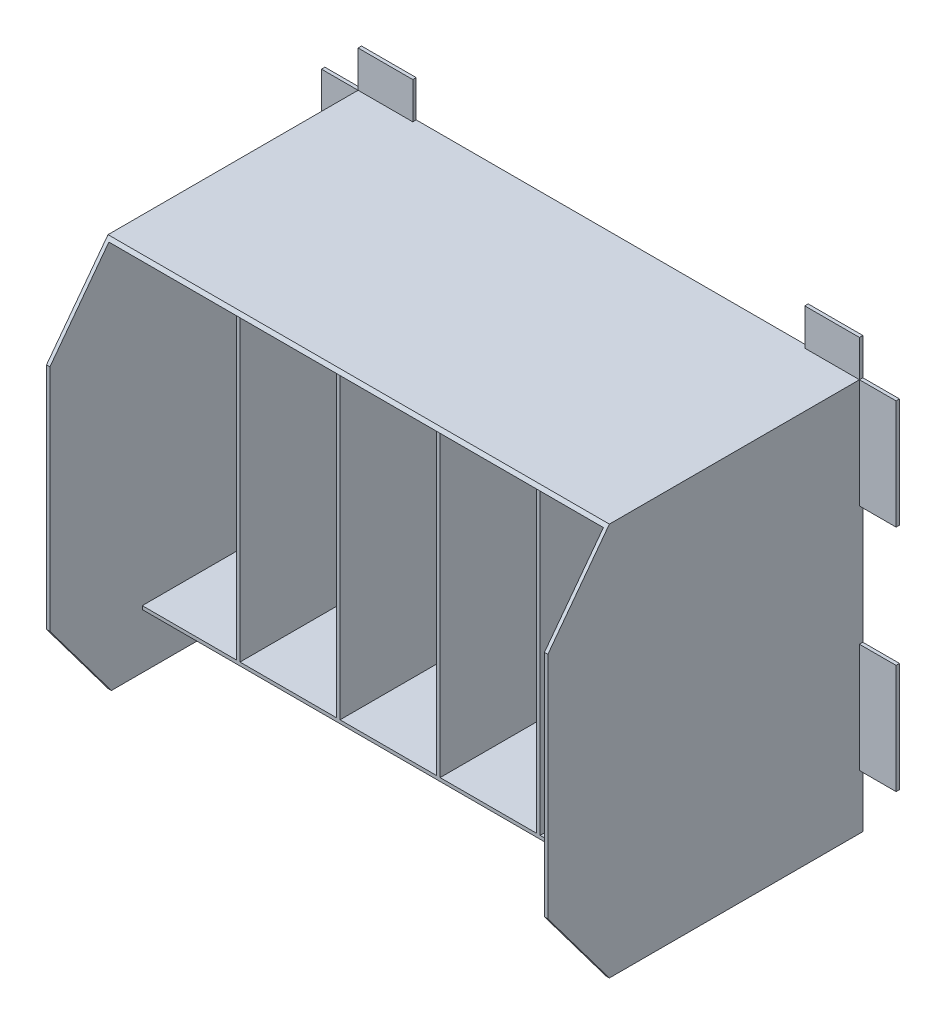
SolidWorks part; units mm, degrees
material "6061-T6 (SS)"
ref_plane "X-Y Datum" through (0, 0, 0) normal (0, 0, 1) x (1, 0, 0)
ref_plane "X-Z Datum" through (0, 0, 0) normal (0, 1, 0) x (1, 0, 0)
ref_plane "Y-Z Datum" through (0, 0, 0) normal (1, 0, 0) x (0, 0, -1)
sketch "Sketch1" plane through (0, 0, 0) normal (0, 0, 1) x (1, 0, 0)
  line L0 (-276.2265, 0) -> (276.2265, 0) construction
  line L1 (-276.2265, 154.041) -> (276.2265, 154.041)
  line L2 (-276.2265, 154.041) -> (-276.2265, -154.041)
  line L3 (-276.2265, -154.041) -> (276.2265, -154.041)
  line L4 (276.2265, 154.041) -> (276.2265, -154.041)
  line L5 (-276.2265, 154.041) -> (276.2265, -154.041) construction
  line L6 (-276.2265, -154.041) -> (276.2265, 154.041) construction
  line L7 (-275.2105, 153.025) -> (-189.6105, 153.025) construction
  line L8 (-275.2105, 153.025) -> (-275.2105, -153.025) construction
  line L9 (-275.2105, -153.025) -> (-189.6105, -153.025) construction
  line L10 (-189.6105, 153.025) -> (-189.6105, -153.025) construction
  line L11 (-275.2105, 153.025) -> (-189.6105, -153.025) construction
  line L12 (-275.2105, -153.025) -> (-189.6105, 153.025) construction
  line L13 (-188.5945, -154.041) -> (-188.5945, 154.041)
  line L14 (-279.4015, 157.216) -> (279.4015, 157.216)
  line L15 (279.4015, 157.216) -> (279.4015, -157.216)
  line L16 (-279.4015, -157.216) -> (279.4015, -157.216)
  line L17 (-279.4015, 157.216) -> (-279.4015, -157.216)
  line L18 (-185.4195, -154.041) -> (-185.4195, 154.041)
  line L19 (-188.5945, 0) -> (-185.4195, 0) construction
  line L20 (-182.2465, 153.025) -> (-182.2465, -153.025) construction
  line L21 (-182.2465, 153.025) -> (-96.6465, 153.025) construction
  line L22 (-96.6465, 153.025) -> (-96.6465, -153.025) construction
  line L23 (-182.2465, -153.025) -> (-96.6465, -153.025) construction
  line L24 (-95.6305, -154.041) -> (-95.6305, 154.041)
  line L25 (-92.4555, -154.041) -> (-92.4555, 154.041)
  line L26 (-89.2825, 153.025) -> (-89.2825, -153.025) construction
  line L27 (-89.2825, 153.025) -> (-3.6825, 153.025) construction
  line L28 (-3.6825, 153.025) -> (-3.6825, -153.025) construction
  line L29 (-89.2825, -153.025) -> (-3.6825, -153.025) construction
  line L30 (-2.6665, -154.041) -> (-2.6665, 154.041)
  line L31 (0.5085, -154.041) -> (0.5085, 154.041)
  line L32 (3.6815, 153.025) -> (3.6815, -153.025) construction
  line L33 (3.6815, 153.025) -> (89.2815, 153.025) construction
  line L34 (89.2815, 153.025) -> (89.2815, -153.025) construction
  line L35 (3.6815, -153.025) -> (89.2815, -153.025) construction
  line L36 (90.2975, -154.041) -> (90.2975, 154.041)
  line L37 (93.4725, -154.041) -> (93.4725, 154.041)
  line L38 (96.6455, 153.025) -> (96.6455, -153.025) construction
  line L39 (96.6455, 153.025) -> (182.2455, 153.025) construction
  line L40 (182.2455, 153.025) -> (182.2455, -153.025) construction
  line L41 (96.6455, -153.025) -> (182.2455, -153.025) construction
  line L42 (183.2615, -154.041) -> (183.2615, 154.041)
  line L43 (186.4365, -154.041) -> (186.4365, 154.041)
  line L44 (-182.2465, -153.025) -> (-96.6465, 153.025) construction
  line L45 (-182.2465, 153.025) -> (-96.6465, -153.025) construction
  line L46 (-89.2825, -153.025) -> (-3.6825, 153.025) construction
  line L47 (-89.2825, 153.025) -> (-3.6825, -153.025) construction
  line L48 (3.6815, -153.025) -> (89.2815, 153.025) construction
  line L49 (3.6815, 153.025) -> (89.2815, -153.025) construction
  line L50 (96.6455, -153.025) -> (182.2455, 153.025) construction
  line L51 (96.6455, 153.025) -> (182.2455, -153.025) construction
  line L52 (-276.2265, -157.216) -> (-276.2265, -204.841)
  line L53 (-279.4015, -157.216) -> (279.4015, -157.216)
  line L54 (-279.4015, -157.216) -> (-279.4015, -208.016)
  line L55 (-279.4015, -208.016) -> (279.4015, -208.016)
  line L56 (279.4015, -157.216) -> (279.4015, -208.016)
  line L57 (-276.2265, -204.841) -> (276.2265, -204.841)
  line L58 (276.2265, -157.216) -> (276.2265, -204.841)
  line L59 (186.4365, -154.041) -> (186.4365, -208.016)
  line L60 (183.2615, -157.216) -> (183.2615, -204.841)
  line L61 (186.4365, 154.041) -> (186.4365, 157.216)
  point P0 (0, 0)
  point P6 (-232.4105, 0)
  point P23 (-187.007, 0)
  point P24 (-139.4465, 0)
  dimension "D1" = 306.05
  dimension "D2" = 85.6
  dimension "D3" = 1.016
  dimension "D4" = 1.016
  dimension "D5" = 1.016
  dimension "D8" = 45.4035
  dimension "D10" = 89.789
  dimension "D12" = 92.964
  dimension "D13" = 89.79
  dimension "D14" = 50.8
  dimension "D6" = 3.175
  dimension "D7" = 3.175
  dimension "D15" = 3.175
  dimension "D9" = 5
  dimension "D11" = 5
extrude "Boss-Extrude1" add sketch "Sketch1" along normal blind 3.175 contours L60 L16 L52 L57 | L53 L60 L57 L59 | L59 L57 L52 L16 L54 L55 | L1 L61 L14 L17 L16 L53 L59 L3 L2 | L3 L42 L1 L37 | L3 L43 L1 L42 | L3 L36 L1 L31 | L3 L37 L1 L36 | L3 L30 L1 L25 | L3 L24 L1 L18 | L3 L13 L1 L2 | L3 L18 L1 L13 | L3 L25 L1 L24 | L3 L31 L1 L30
sketch "Sketch2" plane through (0, 0, 3.175) normal (0, 0, 1) x (1, 0, 0)
  line L0 (-188.5945, -154.041) -> (-188.5945, 154.041) construction
  line L1 (-95.6305, -154.041) -> (-95.6305, 154.041) construction
  line L2 (-185.4195, -154.041) -> (-185.4195, 154.041) construction
  line L3 (90.2975, -154.041) -> (90.2975, 154.041) construction
  line L4 (276.2265, 154.041) -> (-276.2265, 154.041)
  line L5 (276.2265, -154.041) -> (276.2265, 154.041)
  line L6 (-276.2265, -154.041) -> (276.2265, -154.041)
  line L7 (-276.2265, 154.041) -> (-276.2265, -154.041)
  line L8 (276.2265, 154.041) -> (-276.2265, 154.041)
  line L9 (276.2265, -154.041) -> (276.2265, 154.041)
  line L10 (-276.2265, -154.041) -> (276.2265, -154.041)
  line L11 (-276.2265, 154.041) -> (-276.2265, -154.041)
  line L12 (-279.4015, -157.216) -> (279.4015, -157.216)
  line L13 (-279.4015, -157.216) -> (279.4015, -157.216) construction
  line L14 (279.4015, 157.216) -> (279.4015, -157.216) construction
  line L15 (-279.4015, 157.216) -> (279.4015, 157.216) construction
  line L16 (-279.4015, -157.216) -> (279.4015, -157.216)
  line L20 (0.5085, -154.041) -> (0.5085, 154.041) construction
  line L21 (-2.6665, -154.041) -> (-2.6665, 154.041) construction
  line L22 (-92.4555, -154.041) -> (-92.4555, 154.041) construction
  line L23 (186.4365, -154.041) -> (186.4365, 154.041) construction
  line L24 (183.2615, -154.041) -> (183.2615, 154.041) construction
  line L25 (93.4725, -154.041) -> (93.4725, 154.041) construction
  line L26 (-188.5945, -154.041) -> (-188.5945, 154.041)
  line L27 (-95.6305, -154.041) -> (-95.6305, 154.041)
  line L28 (-185.4195, -154.041) -> (-185.4195, 154.041)
  line L29 (90.2975, -154.041) -> (90.2975, 154.041)
  line L30 (0.5085, -154.041) -> (0.5085, 154.041)
  line L31 (-2.6665, -154.041) -> (-2.6665, 154.041)
  line L32 (-92.4555, -154.041) -> (-92.4555, 154.041)
  line L33 (186.4365, -154.041) -> (186.4365, 154.041)
  line L34 (183.2615, -154.041) -> (183.2615, 154.041)
  line L35 (93.4725, -154.041) -> (93.4725, 154.041)
  line L36 (-279.4015, 157.216) -> (-279.4015, -157.216) construction
  line L37 (-279.4015, -157.216) -> (279.4015, -157.216) construction
  line L38 (-279.4015, -157.216) -> (-279.4015, -208.016) construction
  line L39 (-279.4015, -208.016) -> (279.4015, -208.016) construction
  line L40 (279.4015, -157.216) -> (279.4015, -208.016) construction
  line L41 (-276.2265, -157.216) -> (-276.2265, -204.841) construction
  line L42 (-276.2265, -204.841) -> (276.2265, -204.841) construction
  line L43 (276.2265, -157.216) -> (276.2265, -204.841) construction
  line L44 (-276.2265, 154.041) -> (276.2265, 154.041) construction
  line L45 (276.2265, 154.041) -> (276.2265, -154.041) construction
  line L46 (-276.2265, -154.041) -> (276.2265, -154.041) construction
  line L47 (-276.2265, 154.041) -> (-276.2265, -154.041) construction
  line L48 (-188.5945, -154.041) -> (-188.5945, 154.041)
  line L49 (-95.6305, -154.041) -> (-95.6305, 154.041)
  line L50 (-185.4195, -154.041) -> (-185.4195, 154.041)
  line L51 (-279.4015, -157.216) -> (279.4015, -157.216)
  line L52 (279.4015, 157.216) -> (279.4015, -157.216)
  line L53 (-279.4015, 157.216) -> (279.4015, 157.216)
  line L54 (-279.4015, 157.216) -> (-279.4015, -157.216)
  line L55 (-279.4015, -157.216) -> (279.4015, -157.216)
  line L56 (-279.4015, -157.216) -> (-279.4015, -208.016)
  line L57 (-279.4015, -208.016) -> (279.4015, -208.016)
  line L58 (279.4015, -157.216) -> (279.4015, -208.016)
  line L59 (90.2975, -154.041) -> (90.2975, 154.041)
  line L60 (0.5085, -154.041) -> (0.5085, 154.041)
  line L61 (-2.6665, -154.041) -> (-2.6665, 154.041)
  line L62 (-92.4555, -154.041) -> (-92.4555, 154.041)
  line L63 (186.4365, -154.041) -> (186.4365, 154.041)
  line L64 (183.2615, -154.041) -> (183.2615, 154.041)
  line L65 (93.4725, -154.041) -> (93.4725, 154.041)
  line L66 (-276.2265, -157.216) -> (-276.2265, -204.841)
  line L67 (-276.2265, -204.841) -> (276.2265, -204.841)
  line L68 (276.2265, -157.216) -> (276.2265, -204.841)
  line L69 (-276.2265, 154.041) -> (276.2265, 154.041)
  line L70 (276.2265, 154.041) -> (276.2265, -154.041)
  line L71 (-276.2265, -154.041) -> (276.2265, -154.041)
  line L72 (-276.2265, 154.041) -> (-276.2265, -154.041)
  line L73 (183.2615, -157.216) -> (183.2615, -204.841) construction
  line L74 (186.4365, 154.041) -> (186.4365, 157.216) construction
  line L75 (186.4365, -154.041) -> (186.4365, -208.016) construction
  line L76 (-188.5945, -154.041) -> (-188.5945, 154.041)
  line L77 (-95.6305, -154.041) -> (-95.6305, 154.041)
  line L78 (-185.4195, -154.041) -> (-185.4195, 154.041)
  line L79 (-279.4015, -157.216) -> (279.4015, -157.216)
  line L80 (279.4015, 157.216) -> (279.4015, -157.216)
  line L81 (-279.4015, 157.216) -> (279.4015, 157.216)
  line L82 (-279.4015, 157.216) -> (-279.4015, -157.216)
  line L83 (-279.4015, -157.216) -> (279.4015, -157.216)
  line L84 (-279.4015, -157.216) -> (-279.4015, -208.016)
  line L85 (-279.4015, -208.016) -> (279.4015, -208.016)
  line L86 (279.4015, -157.216) -> (279.4015, -208.016)
  line L87 (90.2975, -154.041) -> (90.2975, 154.041)
  line L88 (0.5085, -154.041) -> (0.5085, 154.041)
  line L89 (-2.6665, -154.041) -> (-2.6665, 154.041)
  line L90 (-92.4555, -154.041) -> (-92.4555, 154.041)
  line L91 (183.2615, -154.041) -> (183.2615, 154.041)
  line L92 (93.4725, -154.041) -> (93.4725, 154.041)
  line L93 (183.2615, -157.216) -> (183.2615, -204.841)
  line L94 (-276.2265, -157.216) -> (-276.2265, -204.841)
  line L95 (-276.2265, -204.841) -> (276.2265, -204.841)
  line L96 (276.2265, -157.216) -> (276.2265, -204.841)
  line L97 (186.4365, 154.041) -> (186.4365, 157.216)
  line L98 (186.4365, -154.041) -> (186.4365, 154.041)
  line L99 (186.4365, -154.041) -> (186.4365, -208.016)
  line L100 (-276.2265, 154.041) -> (276.2265, 154.041)
  line L101 (276.2265, 154.041) -> (276.2265, -154.041)
  line L102 (-276.2265, -154.041) -> (276.2265, -154.041)
  line L103 (-276.2265, 154.041) -> (-276.2265, -154.041)
  dimension "D1" = 0
  dimension "D2" = 0
extrude "Boss-Extrude2" add sketch "Sketch2" along normal blind 200.6
sketch "Sketch4" plane through (0, -208.016, 0) normal (0, -1, 0) x (1, 0, 0)
  line L0 (-276.2265, 203.775) -> (-276.2265, 3.175)
  line L1 (-276.2265, 3.175) -> (183.2615, 3.175)
  line L2 (183.2615, 3.175) -> (183.2615, 203.775)
  line L4 (-279.4015, 0) -> (186.4365, 0)
  line L5 (186.4365, 0) -> (186.4365, 203.775)
  line L6 (186.4365, 203.775) -> (-279.4015, 203.775)
  line L7 (-279.4015, 203.775) -> (-279.4015, 0)
  line L8 (-279.4015, 0) -> (186.4365, 0)
  line L11 (-279.4015, 203.775) -> (-279.4015, 0)
  line L15 (186.4365, 203.775) -> (-279.4015, 203.775)
  line L16 (186.4365, 0) -> (186.4365, 203.775) construction
  line L18 (186.4365, 0) -> (186.4365, 203.775)
  dimension "D1" = 0
  dimension "D2" = 3.175
extrude "Cut-Extrude1" cut sketch "Sketch4" against normal blind 3.175
sketch "Sketch5" plane through (0, 0, 203.775) normal (0, 0, 1) x (1, 0, 0)
  line L0 (-188.5945, -154.041) -> (-188.5945, 154.041) construction
  line L1 (-95.6305, -154.041) -> (-95.6305, 154.041) construction
  line L2 (-185.4195, -154.041) -> (-185.4195, 154.041) construction
  line L3 (-279.4015, -157.216) -> (279.4015, -157.216) construction
  line L4 (279.4015, 157.216) -> (279.4015, -157.216) construction
  line L5 (-279.4015, 157.216) -> (279.4015, 157.216) construction
  line L6 (-279.4015, 157.216) -> (-279.4015, -157.216) construction
  line L7 (-279.4015, -157.216) -> (279.4015, -157.216) construction
  line L8 (-279.4015, -157.216) -> (-279.4015, -208.016) construction
  line L9 (-279.4015, -208.016) -> (279.4015, -208.016) construction
  line L10 (279.4015, -157.216) -> (279.4015, -208.016) construction
  line L11 (90.2975, -154.041) -> (90.2975, 154.041) construction
  line L12 (0.5085, -154.041) -> (0.5085, 154.041) construction
  line L13 (-2.6665, -154.041) -> (-2.6665, 154.041) construction
  line L14 (-92.4555, -154.041) -> (-92.4555, 154.041) construction
  line L15 (186.4365, -154.041) -> (186.4365, 154.041) construction
  line L16 (183.2615, -154.041) -> (183.2615, 154.041) construction
  line L17 (93.4725, -154.041) -> (93.4725, 154.041) construction
  line L18 (-276.2265, -157.216) -> (-276.2265, -204.841) construction
  line L19 (-276.2265, -204.841) -> (276.2265, -204.841) construction
  line L20 (276.2265, -157.216) -> (276.2265, -204.841) construction
  line L21 (-276.2265, 154.041) -> (276.2265, 154.041) construction
  line L22 (276.2265, 154.041) -> (276.2265, -154.041) construction
  line L23 (-276.2265, -154.041) -> (276.2265, -154.041) construction
  line L24 (-276.2265, 154.041) -> (-276.2265, -154.041) construction
  line L25 (-188.5945, -154.041) -> (-188.5945, 154.041)
  line L26 (-95.6305, -154.041) -> (-95.6305, 154.041)
  line L27 (-185.4195, -154.041) -> (-185.4195, 154.041)
  line L28 (-279.4015, -157.216) -> (279.4015, -157.216)
  line L29 (279.4015, 157.216) -> (279.4015, -157.216)
  line L30 (-279.4015, 157.216) -> (279.4015, 157.216)
  line L31 (-279.4015, 157.216) -> (-279.4015, -157.216)
  line L32 (-279.4015, -157.216) -> (279.4015, -157.216)
  line L33 (-279.4015, -157.216) -> (-279.4015, -208.016)
  line L34 (-279.4015, -208.016) -> (279.4015, -208.016)
  line L35 (279.4015, -157.216) -> (279.4015, -208.016)
  line L36 (90.2975, -154.041) -> (90.2975, 154.041)
  line L37 (0.5085, -154.041) -> (0.5085, 154.041)
  line L38 (-2.6665, -154.041) -> (-2.6665, 154.041)
  line L39 (-92.4555, -154.041) -> (-92.4555, 154.041)
  line L40 (186.4365, -154.041) -> (186.4365, 154.041)
  line L41 (183.2615, -154.041) -> (183.2615, 154.041)
  line L42 (93.4725, -154.041) -> (93.4725, 154.041)
  line L43 (-276.2265, -157.216) -> (-276.2265, -204.841)
  line L44 (-276.2265, -204.841) -> (276.2265, -204.841)
  line L45 (276.2265, -157.216) -> (276.2265, -204.841)
  line L46 (-276.2265, 154.041) -> (276.2265, 154.041)
  line L47 (276.2265, 154.041) -> (276.2265, -154.041)
  line L48 (-276.2265, -154.041) -> (276.2265, -154.041)
  line L49 (-276.2265, 154.041) -> (-276.2265, -154.041)
  line M1 (93.4725, 154.041) -> (183.2615, 154.041)
  line M2 (183.2615, 154.041) -> (183.2615, -154.041)
  line M3 (183.2615, -154.041) -> (93.4725, -154.041)
  line M4 (93.4725, -154.041) -> (93.4725, 154.041)
  line M5 (0.5085, 154.041) -> (90.2975, 154.041)
  line M6 (90.2975, 154.041) -> (90.2975, -154.041)
  line M7 (90.2975, -154.041) -> (0.5085, -154.041)
  line M8 (0.5085, -154.041) -> (0.5085, 154.041)
  line M9 (-92.4555, 154.041) -> (-2.6665, 154.041)
  line M10 (-2.6665, 154.041) -> (-2.6665, -154.041)
  line M11 (-2.6665, -154.041) -> (-92.4555, -154.041)
  line M12 (-92.4555, -154.041) -> (-92.4555, 154.041)
  line M13 (-185.4195, 154.041) -> (-95.6305, 154.041)
  line M14 (-95.6305, 154.041) -> (-95.6305, -154.041)
  line M15 (-95.6305, -154.041) -> (-185.4195, -154.041)
  line M16 (-185.4195, -154.041) -> (-185.4195, 154.041)
  line M17 (-276.2265, 154.041) -> (-188.5945, 154.041)
  line M18 (-188.5945, 154.041) -> (-188.5945, -154.041)
  line M19 (-188.5945, -154.041) -> (-276.2265, -154.041)
  line M20 (-276.2265, -154.041) -> (-276.2265, 154.041)
  line M21 (-276.2265, -208.016) -> (-276.2265, -157.216)
  line M22 (-276.2265, -157.216) -> (183.2615, -157.216)
  line M25 (186.4365, -208.016) -> (186.4365, 157.216)
  line M29 (-279.4015, 157.216) -> (-279.4015, -208.016)
  line M30 (-279.4015, -208.016) -> (-276.2265, -208.016)
  line M32 (186.4365, 157.216) -> (-279.4015, 157.216)
  line M85 (183.2615, -157.216) -> (183.2615, -208.016)
  line M86 (183.2615, -208.016) -> (186.4365, -208.016)
extrude "Boss-Extrude5" add sketch "Sketch5" along normal blind 38.1 contours L44 M85 M86 M25 | L44 L28 M85 M25 | L48 L46 M2 M25 | L48 L46 L28 M19 M20 M17 M13 M9 M5 M1 M25 M32 M29 M22 M3 M7 M11 M15 | L48 L46 M6 M4 | L48 L46 M10 M8 | L48 L46 M14 M12 | L48 L46 M18 M16 | L28 M29 M30 M21 | L33 L34 L35 | L41
sketch "Sketch7" plane through (0, 0, 241.875) normal (0, 0, 1) x (1, 0, 0)
  line L0 (-188.5945, -154.041) -> (-188.5945, 154.041) construction
  line L1 (-95.6305, -154.041) -> (-95.6305, 154.041) construction
  line L2 (-185.4195, -154.041) -> (-185.4195, 154.041) construction
  line L3 (-279.4015, -157.216) -> (279.4015, -157.216) construction
  line L4 (279.4015, 157.216) -> (279.4015, -157.216) construction
  line L5 (-279.4015, 157.216) -> (279.4015, 157.216) construction
  line L6 (-279.4015, 157.216) -> (-279.4015, -157.216) construction
  line L7 (-279.4015, -157.216) -> (279.4015, -157.216) construction
  line L8 (-279.4015, -157.216) -> (-279.4015, -208.016) construction
  line L9 (-279.4015, -208.016) -> (279.4015, -208.016) construction
  line L10 (279.4015, -157.216) -> (279.4015, -208.016) construction
  line L11 (90.2975, -154.041) -> (90.2975, 154.041) construction
  line L12 (0.5085, -154.041) -> (0.5085, 154.041) construction
  line L13 (-2.6665, -154.041) -> (-2.6665, 154.041) construction
  line L14 (-92.4555, -154.041) -> (-92.4555, 154.041) construction
  line L15 (186.4365, -154.041) -> (186.4365, 154.041) construction
  line L16 (183.2615, -154.041) -> (183.2615, 154.041) construction
  line L17 (93.4725, -154.041) -> (93.4725, 154.041) construction
  line L18 (-276.2265, -157.216) -> (-276.2265, -204.841) construction
  line L19 (-276.2265, -204.841) -> (276.2265, -204.841) construction
  line L20 (276.2265, -157.216) -> (276.2265, -204.841) construction
  line L21 (-276.2265, 154.041) -> (276.2265, 154.041) construction
  line L22 (276.2265, 154.041) -> (276.2265, -154.041) construction
  line L23 (-276.2265, -154.041) -> (276.2265, -154.041) construction
  line L24 (-276.2265, 154.041) -> (-276.2265, -154.041) construction
  line L25 (-188.5945, -154.041) -> (-188.5945, 154.041)
  line L26 (-95.6305, -154.041) -> (-95.6305, 154.041)
  line L27 (-185.4195, -154.041) -> (-185.4195, 154.041)
  line L28 (-279.4015, -157.216) -> (279.4015, -157.216)
  line L29 (279.4015, 157.216) -> (279.4015, -157.216)
  line L30 (-279.4015, 157.216) -> (279.4015, 157.216)
  line L31 (-279.4015, 157.216) -> (-279.4015, -157.216)
  line L32 (-279.4015, -157.216) -> (279.4015, -157.216)
  line L33 (-279.4015, -157.216) -> (-279.4015, -208.016)
  line L34 (-279.4015, -208.016) -> (279.4015, -208.016)
  line L35 (279.4015, -157.216) -> (279.4015, -208.016)
  line L36 (90.2975, -154.041) -> (90.2975, 154.041)
  line L37 (0.5085, -154.041) -> (0.5085, 154.041)
  line L38 (-2.6665, -154.041) -> (-2.6665, 154.041)
  line L39 (-92.4555, -154.041) -> (-92.4555, 154.041)
  line L40 (186.4365, -154.041) -> (186.4365, 154.041)
  line L41 (183.2615, -154.041) -> (183.2615, 154.041)
  line L42 (93.4725, -154.041) -> (93.4725, 154.041)
  line L43 (-276.2265, -157.216) -> (-276.2265, -204.841)
  line L44 (-276.2265, -204.841) -> (276.2265, -204.841)
  line L45 (276.2265, -157.216) -> (276.2265, -204.841)
  line L46 (-276.2265, 154.041) -> (276.2265, 154.041)
  line L47 (276.2265, 154.041) -> (276.2265, -154.041)
  line L48 (-276.2265, -154.041) -> (276.2265, -154.041)
  line L49 (-276.2265, 154.041) -> (-276.2265, -154.041)
  line L50 (-276.2265, -154.041) -> (-276.2265, -157.216)
  line L51 (276.2265, -154.041) -> (276.2265, -157.216)
  line L52 (183.2615, -154.041) -> (186.4365, -154.041)
  line L53 (183.2615, 154.041) -> (186.4365, 154.041)
  line L54 (183.2615, -154.041) -> (183.2615, -157.216)
  line M1 (-95.6305, -154.041) -> (-185.4195, -154.041)
  line M2 (-185.4195, -154.041) -> (-185.4195, 154.041)
  line M4 (-95.6305, 154.041) -> (-95.6305, -154.041)
  line M5 (-2.6665, -154.041) -> (-92.4555, -154.041)
  line M6 (-92.4555, -154.041) -> (-92.4555, 154.041)
  line M8 (-2.6665, 154.041) -> (-2.6665, -154.041)
  line M9 (90.2975, -154.041) -> (0.5085, -154.041)
  line M10 (0.5085, -154.041) -> (0.5085, 154.041)
  line M12 (90.2975, 154.041) -> (90.2975, -154.041)
  line M13 (183.2615, -154.041) -> (93.4725, -154.041)
  line M14 (93.4725, -154.041) -> (93.4725, 154.041)
  line M21 (-188.5945, -154.041) -> (-276.2265, -154.041)
  line M24 (-188.5945, 154.041) -> (-188.5945, -154.041)
  line M28 (-276.2265, -157.216) -> (183.2615, -157.216)
extrude "Cut-Extrude2" cut sketch "Sketch7" against normal blind 35 contours L54 L48 L50 M13 M9 M5 M1 M21 M28 | L48 L46 M12 M14 | L48 L46 M4 M6 | L48 L46 M8 M10 | L48 L46 M24 M2 | L36
sketch "Sketch8" plane through (0, 0, 241.875) normal (0, 0, 1) x (1, 0, 0)
  line L8 (183.2615, 154.041) -> (183.2615, -208.016)
  line L9 (183.2615, -208.016) -> (186.4365, -208.016)
  line L10 (186.4365, -208.016) -> (186.4365, 157.216)
  line L11 (186.4365, 157.216) -> (-279.4015, 157.216)
  line L12 (-279.4015, 157.216) -> (-279.4015, -208.016)
  line L13 (-279.4015, -208.016) -> (-276.2265, -208.016)
  line L14 (-276.2265, -208.016) -> (-276.2265, 154.041)
  line L15 (-276.2265, 154.041) -> (183.2615, 154.041)
  line L16 (183.2615, 154.041) -> (183.2615, -208.016)
  line L17 (183.2615, -208.016) -> (186.4365, -208.016)
  line L18 (186.4365, -208.016) -> (186.4365, 157.216)
  line L19 (186.4365, 157.216) -> (-279.4015, 157.216)
  line L20 (-279.4015, 157.216) -> (-279.4015, -208.016)
  line L21 (-279.4015, -208.016) -> (-276.2265, -208.016)
  line L22 (-276.2265, -208.016) -> (-276.2265, 154.041)
  line L23 (-276.2265, 154.041) -> (183.2615, 154.041)
  dimension "D1" = 0
extrude "Boss-Extrude6" add sketch "Sketch8" along normal blind 50.8
sketch "Sketch9" plane through (186.4365, 0, 0) normal (1, 0, 0) x (0, 0, -1)
  line L0 (-235.525, -208.016) -> (-292.675, -131.816)
  line L1 (-292.675, -208.016) -> (0, -208.016) construction
  line L2 (-235.525, 157.216) -> (-292.675, 81.016)
  line L4 (0, -208.016) -> (0, 157.216)
  line L5 (0, 157.216) -> (-292.675, 157.216)
  line L6 (-292.675, 157.216) -> (-292.675, -208.016)
  line L7 (-292.675, -208.016) -> (0, -208.016)
  line L8 (0, -208.016) -> (0, 157.216)
  line L9 (0, 157.216) -> (-292.675, 157.216)
  line L10 (-292.675, 157.216) -> (-292.675, -208.016)
  line L11 (-292.675, -208.016) -> (0, -208.016)
  line M6 (0, 157.216) -> (-292.675, 157.216)
  line M7 (-292.675, 157.216) -> (-292.675, -208.016)
  line M8 (-292.675, -208.016) -> (0, -208.016)
  dimension "D2" = 57.15
  dimension "D3" = 76.2
  dimension "D4" = 76.2
  dimension "D5" = 57.15
  dimension "D1" = 0
extrude "Cut-Extrude3" cut sketch "Sketch9" against normal through all contours L0 M8 M7 | L2 M6 M7
sketch "Sketch10" plane through (0, 0, 0) normal (0, 0, 1) x (1, 0, 0)
  line L0 (-276.2265, -157.216) -> (183.2615, -157.216) construction
  line L1 (186.4365, 157.216) -> (220.4725, 157.216)
  line L2 (186.4365, 157.216) -> (186.4365, 55.616)
  line L3 (186.4365, 55.616) -> (220.4725, 55.616)
  line L4 (186.4365, -208.016) -> (186.4365, 157.216)
  line L5 (-279.4015, -208.016) -> (186.4365, -208.016)
  line L6 (-279.4015, 157.216) -> (-279.4015, -208.016)
  line L7 (186.4365, 157.216) -> (-279.4015, 157.216)
  line L8 (186.4365, -208.016) -> (186.4365, 157.216)
  line L9 (-279.4015, -208.016) -> (186.4365, -208.016)
  line L10 (-279.4015, 157.216) -> (-279.4015, -208.016)
  line L11 (186.4365, 157.216) -> (-279.4015, 157.216)
  line L12 (220.4725, 157.216) -> (220.4725, 55.616)
  line L13 (-276.2265, -157.216) -> (183.2615, -157.216)
  line L15 (186.4365, -157.216) -> (220.4725, -157.216)
  line L16 (186.4365, -157.216) -> (186.4365, -55.616)
  line L17 (186.4365, -55.616) -> (220.4725, -55.616)
  line L18 (220.4725, -157.216) -> (220.4725, -55.616)
  line L19 (186.4365, 157.216) -> (135.6365, 157.216)
  line L20 (186.4365, 157.216) -> (186.4365, 191.252)
  line L21 (186.4365, 191.252) -> (135.6365, 191.252)
  line L22 (135.6365, 157.216) -> (135.6365, 191.252)
  dimension "D2" = 34.036
  dimension "D3" = 101.6
  dimension "D4" = 50.8
  dimension "D1" = 0
extrude "Boss-Extrude7" add sketch "Sketch10" along normal blind 3.175 contours L12 L1 L2 L3 | L15 L18 L17 L8 | L22 L11 L20 L21
ref_plane "Plane1" through (-46.4825, 0, 0) normal (-1, 0, 0) x (0, 0, 1)
mirror "Mirror1" about plane through (-46.4825, 0, 0) normal (-1, 0, 0) of "Boss-Extrude7"
